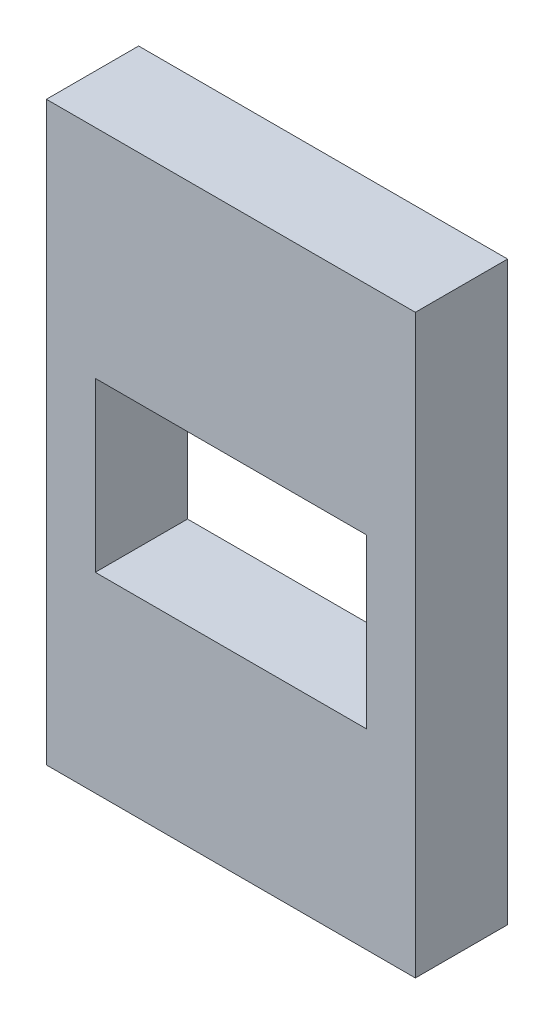
SolidWorks part; units mm, degrees
ref_plane "Plan de face" through (0, 0, 0) normal (0, 0, 1) x (1, 0, 0)
ref_plane "Plan de dessus" through (0, 0, 0) normal (0, 1, 0) x (1, 0, 0)
ref_plane "Plan de droite" through (0, 0, 0) normal (1, 0, 0) x (0, 0, -1)
sketch "Esquisse1" plane through (0, 0, 0) normal (0, 0, 1) x (1, 0, 0)
  line L1 (16, -25) -> (-16, -25)
  line L2 (16, -25) -> (16, 25)
  line L3 (16, 25) -> (-16, 25)
  line L4 (-16, -25) -> (-16, 25)
  line L5 (16, -25) -> (-16, 25) construction
  line L6 (16, 25) -> (-16, -25) construction
  point P0 (0, 0)
  point P6 (0, -25)
  point P7 (16, 0)
  dimension "D1" = 32
  dimension "D2" = 50
extrude "Boss.-Extru.1" add sketch "Esquisse1" along normal blind 8
sketch "Esquisse2" plane through (0, 0, 0) normal (0, 0, -1) x (-1, 0, 0)
  line L0 (-16, 25) -> (16, 25) construction
  line L1 (11.76, -8.41) -> (-11.76, -8.41)
  line L2 (11.76, -8.41) -> (11.76, 6.16)
  line L3 (11.76, 6.16) -> (-11.76, 6.16)
  line L4 (-11.76, -8.41) -> (-11.76, 6.16)
  line L5 (11.76, -8.41) -> (-11.76, 6.16) construction
  line L6 (11.76, 6.16) -> (-11.76, -8.41) construction
  point P0 (0, -1.125)
  point P5 (0, 6.16)
  point P6 (-11.76, -1.125)
  dimension "D1" = 18.84
  dimension "D2" = 23.52
  dimension "D3" = 14.57
extrude "Enlèv. mat.-Extru.1" cut sketch "Esquisse2" against normal blind 8
